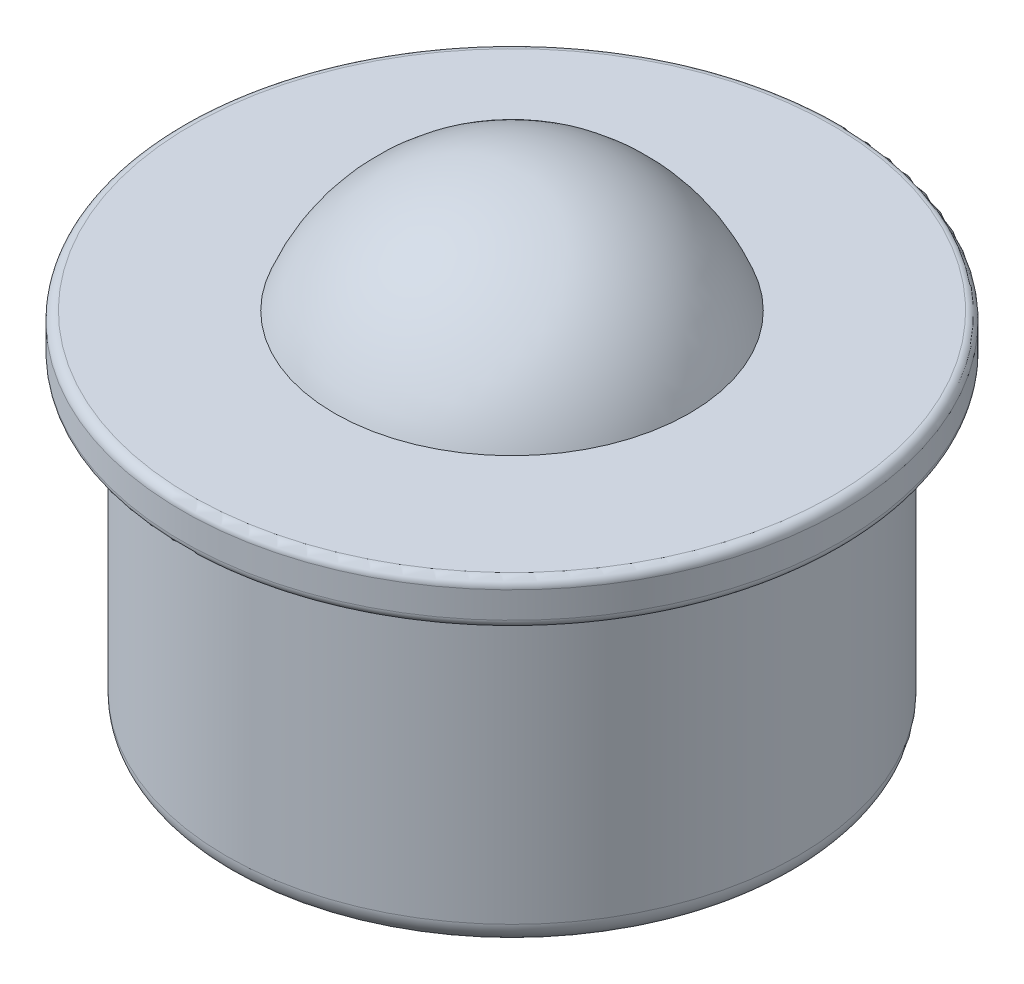
SolidWorks part; units mm, degrees
ref_plane "前视基准面" through (0, 0, 0) normal (0, 0, 1) x (1, 0, 0)
ref_plane "上视基准面" through (0, 0, 0) normal (0, 1, 0) x (1, 0, 0)
ref_plane "右视基准面" through (0, 0, 0) normal (1, 0, 0) x (0, 0, -1)
sketch "草图1" plane through (0, 0, 0) normal (0, 0, 1) x (1, 0, 0)
  line L0 (0, 0) -> (28.8889, 0) construction
  line L1 (0, 28.404) -> (0, -27.9293) construction
  line L2 (4.0438, 8) -> (7.5, 8)
  line L3 (0, 10.8) -> (13.819, 10.8) construction
  line L4 (0, 10.8) -> (0, 0)
  line L5 (0, 0) -> (6.5, 0)
  line L6 (6.5, 7) -> (6.5, 0)
  line L10 (7.5, 8) -> (7.5, 7)
  line L11 (6.5, 7) -> (7.5, 7)
  arc A1 (4.0438, 8) -> (0, 10.8) centre (0, 6.48) ccw
  dimension "D5" = 2.8
  dimension "D4" = 10.8
  dimension "D6" = 8.64
  dimension "D1" = 6.5
  dimension "D2" = 7.5
  dimension "D3" = 7
revolve "旋转4" add sketch "草图1" angle 360 about L1
fillet "圆角1" radius 0.5 1 edges at (-6.5, 0, 0)
fillet "圆角2" radius 0.2 2 edges at (-7.5, 7, 0) (-7.5, 8, 0)
